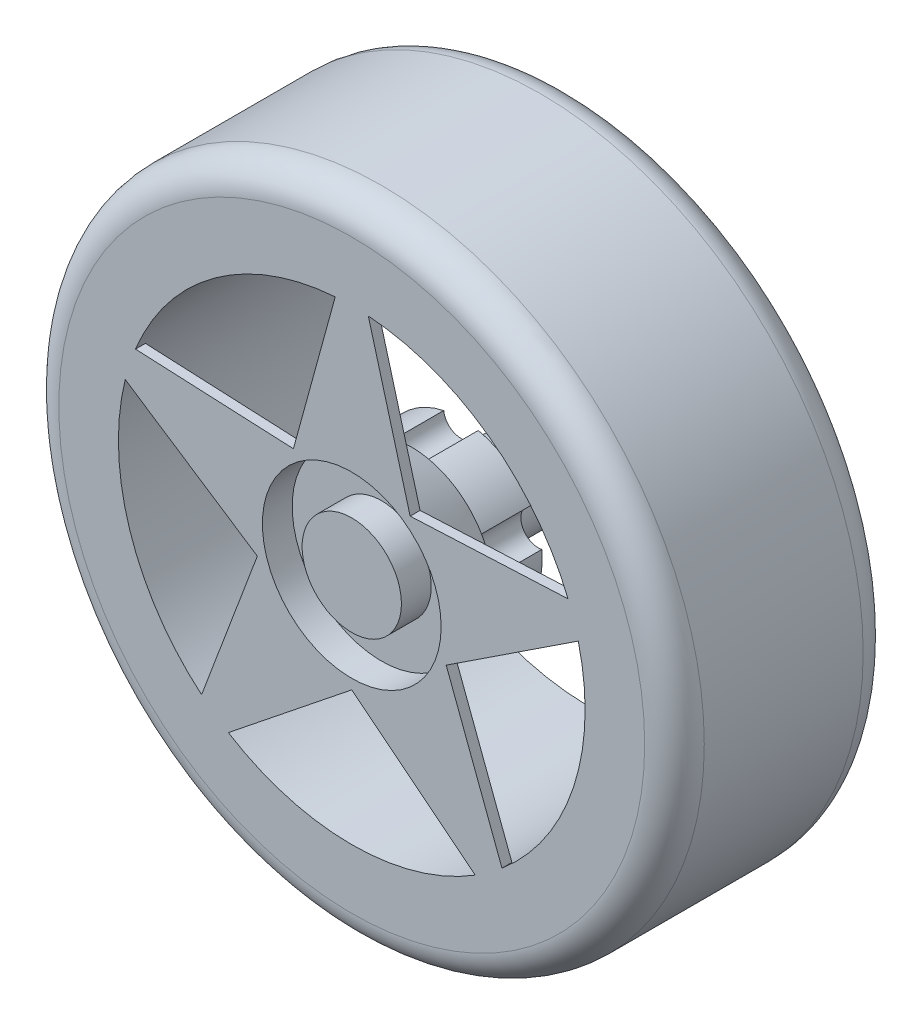
SolidWorks part; units mm, degrees
ref_plane "前视基准面" through (0, 0, 0) normal (0, 0, 1) x (1, 0, 0)
ref_plane "上视基准面" through (0, 0, 0) normal (0, 1, 0) x (1, 0, 0)
ref_plane "右视基准面" through (0, 0, 0) normal (1, 0, 0) x (0, 0, -1)
sketch "草图1" plane through (0, 0, 0) normal (0, 0, 1) x (1, 0, 0)
  line L1 (-2.3365, -1.353) -> (2.3365, -1.353)
  line L3 (-2.34, 1.347) -> (2.34, 1.347)
  line L5 (0, 1.347) -> (0, -1.353) construction
  line L6 (-2.3383, 0) -> (2.3383, 0) construction
  circle A0 centre (0, 0) radius 4
  arc A1 (-2.34, 1.347) -> (-2.3365, -1.353) centre (0, 0) ccw
  arc A2 (2.3365, -1.353) -> (2.34, 1.347) centre (0, 0) ccw
  dimension "D1" = 8
  dimension "D2" = 5.4
  dimension "D3" = 2.7
  dimension "D4" = 4.68
extrude "凸台-拉伸1" add sketch "草图1" along normal blind 30
sketch "草图2" plane through (0, 0, 30) normal (0, 0, 1) x (1, 0, 0)
  circle A0 centre (0, 0) radius 10
  dimension "D1" = 20
extrude "凸台-拉伸2" add sketch "草图2" along normal blind 5
draft "拔模1" type of draft neutral plane draft angle 20 faces to draft 1 face at (10, 0, 35) neutral plane through (0, 0, 35) neutral plane normal (0, 0, 1) reverse direction yes parameters "D1"=20
sketch "草图3" plane through (0, 0, 30) normal (0, 0, -1) x (-1, 0, 0)
  line L0 (0, -1000) -> (0, 6.43) construction
  line L1 (0, 9.93) -> (0, 49000) construction
  arc A0 (-8.1393, 0.8151) -> (-6.1057, -5.4436) centre (0, 0) ccw
  arc A1 (-1.74, 7.9928) -> (1.74, 7.9928) centre (0, 8.18) ccw
  arc A2 (7.0639, 4.1247) -> (8.1393, 0.8151) centre (7.7796, 2.5278) ccw
  arc A3 (6.1057, -5.4436) -> (3.2904, -7.489) centre (4.8081, -6.6178) ccw
  arc A4 (-3.2904, -7.489) -> (-6.1057, -5.4436) centre (-4.8081, -6.6178) ccw
  arc A5 (-8.1393, 0.8151) -> (-7.0639, 4.1247) centre (-7.7796, 2.5278) ccw
  arc A6 (-1.74, 7.9928) -> (-7.0639, 4.1247) centre (0, 0) ccw
  arc A7 (7.0639, 4.1247) -> (1.74, 7.9928) centre (0, 0) ccw
  arc A8 (6.1057, -5.4436) -> (8.1393, 0.8151) centre (0, 0) ccw
  arc A9 (-3.2904, -7.489) -> (3.2904, -7.489) centre (0, 0) ccw
  point P23 (0, 0)
  dimension "D1" = 16.36
  dimension "D2" = 3.5
  dimension "D3" = 5
extrude "凸台-拉伸3" add sketch "草图3" along normal blind 5
sketch "草图4" plane through (0, 0, 35) normal (0, 0, 1) x (1, 0, 0)
  line L0 (0, -1000) -> (0, 49000) construction
  line L1 (-1.375, 24.5) -> (1.375, 24.5)
  line L2 (0, 0) -> (-29389.2626, 40450.8497) construction
  line L3 (-1.375, 24.5) -> (-5.8779, 8.0902)
  line L4 (1.375, 24.5) -> (5.8779, 8.0902)
  line L5 (22.876, 8.8786) -> (5.8779, 8.0902)
  line L6 (23.7258, 6.2632) -> (9.5106, -3.0902)
  line L7 (22.876, 8.8786) -> (23.7258, 6.2632)
  line L8 (15.5131, -19.0127) -> (9.5106, -3.0902)
  line L9 (13.2883, -20.6291) -> (0, -10)
  line L10 (15.5131, -19.0127) -> (13.2883, -20.6291)
  line L11 (-13.2883, -20.6291) -> (0, -10)
  line L12 (-15.5131, -19.0127) -> (-9.5106, -3.0902)
  line L13 (-13.2883, -20.6291) -> (-15.5131, -19.0127)
  line L14 (-23.7258, 6.2632) -> (-9.5106, -3.0902)
  line L15 (-22.876, 8.8786) -> (-5.8779, 8.0902)
  line L16 (-23.7258, 6.2632) -> (-22.876, 8.8786)
  point P8 (0, 24.5)
  point P31 (0, 0)
  dimension "D3" = 2.75
  dimension "D4" = 36
  dimension "D5" = 5
extrude "凸台-拉伸4" add sketch "草图4" along normal blind 1
sketch "草图5" plane through (0, 0, 36) normal (0, 0, 1) x (1, 0, 0)
  circle A0 centre (0, 0) radius 25
  circle A1 centre (0, 0) radius 23.5
  dimension "D1" = 50
  dimension "D2" = 47
extrude "凸台-拉伸5" add sketch "草图5" against normal blind 24
sketch "草图6" plane through (0, 0, 36) normal (0, 0, 1) x (1, 0, 0)
  circle A0 centre (0, 0) radius 9
  circle A1 centre (0, 0) radius 5
  dimension "D1" = 18
  dimension "D2" = 10
extrude "切除-拉伸1" cut sketch "草图6" against normal blind 3
sketch "草图7" plane through (0, 0, 36) normal (0, 0, 1) x (1, 0, 0)
  circle A0 centre (0, 0) radius 32.5
  circle A1 centre (0, 0) radius 25
  dimension "D1" = 65
  dimension "D2" = 50
extrude "凸台-拉伸6" add sketch "草图7" against normal blind 22
fillet "圆角1" radius 3 2 edges at (32.5, 0, 14) (32.5, 0, 36)
